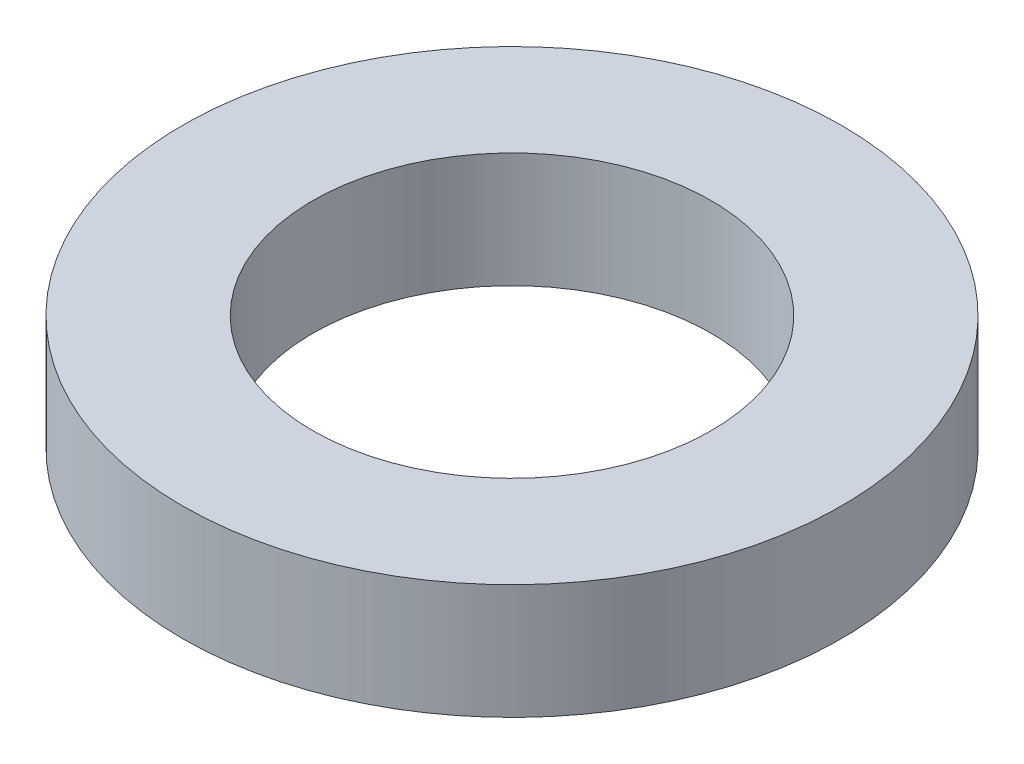
SolidWorks part; units mm, degrees
ref_plane "Front" through (0, 0, 0) normal (0, 0, 1) x (1, 0, 0)
ref_plane "Top" through (0, 0, 0) normal (0, 1, 0) x (1, 0, 0)
ref_plane "Right" through (0, 0, 0) normal (1, 0, 0) x (0, 0, -1)
sketch "Sketch2" plane through (0, 0, 0) normal (0, 1, 0) x (1, 0, 0)
  circle A0 centre (0, 0) radius 43
extrude "Boss-Extrude1" add sketch "Sketch2" along normal blind 15
sketch "Sketch3" plane through (0, 15, 0) normal (0, 1, 0) x (1, 0, 0)
  circle A0 centre (0, 0) radius 26
extrude "Cut-Extrude1" cut sketch "Sketch3" against normal blind 15 contours A0
